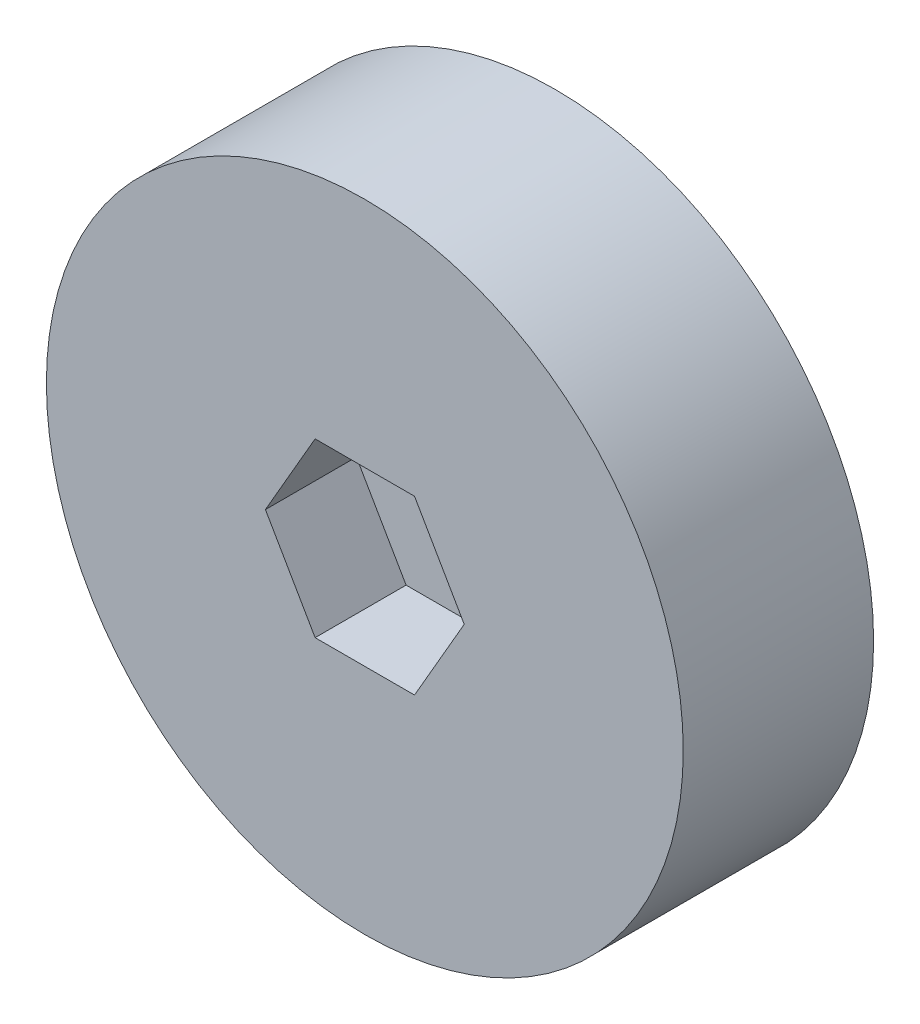
SolidWorks part; units mm, degrees
ref_plane "Front Plane" through (0, 0, 0) normal (0, 0, 1) x (1, 0, 0)
ref_plane "Top Plane" through (0, 0, 0) normal (0, 1, 0) x (1, 0, 0)
ref_plane "Right Plane" through (0, 0, 0) normal (1, 0, 0) x (0, 0, -1)
other "Configuration Table"
sketch "Sketch7" plane through (0, 0, 0) normal (0, 0, 1) x (1, 0, 0)
  circle A0 centre (0, 0) radius 24.25
  dimension "D1" = 48.5
extrude "Boss-Extrude3" [suppressed] add sketch "Sketch7" along normal blind 6.5
sketch "Sketch8" [suppressed] plane through (0, 0, 0) normal (0, 0, -1) x (-1, 0, 0)
  line L1 (3.5507, -6.15) -> (7.1014, 0)
  line L2 (7.1014, 0) -> (3.5507, 6.15)
  line L3 (3.5507, 6.15) -> (-3.5507, 6.15)
  line L4 (-3.5507, 6.15) -> (-7.1014, 0)
  line L5 (-7.1014, 0) -> (-3.5507, -6.15)
  line L6 (-3.5507, -6.15) -> (3.5507, -6.15)
  circle A0 centre (0, 0) radius 6.15 construction
  dimension "D1" = 12.3
extrude "Cut-Extrude4" [suppressed] cut sketch "Sketch8" against normal up to surface (6.5 mm away)
sketch "Sketch9" [suppressed] plane through (0, 0, 0) normal (0, 0, -1) x (-1, 0, 0)
  circle A0 centre (0, 0) radius 24.25 construction
  circle A1 centre (0, 0) radius 24.25
extrude "Boss-Extrude4" [suppressed] add sketch "Sketch9" along normal blind 7.1
sketch "Sketch10" [suppressed] plane through (0, 0, -7.1) normal (0, 0, -1) x (-1, 0, 0)
  circle A0 centre (0, 0) radius 4
  dimension "D1" = 8
extrude "Boss-Extrude5" [suppressed] add sketch "Sketch10" along normal blind 7
sketch "Sketch11" [suppressed] plane through (0, 0, 0) normal (0, 0, 1) x (1, 0, 0)
  circle A0 centre (0, 0) radius 2.2
  dimension "D1" = 4.4
extrude "Cut-Extrude5" [suppressed] cut sketch "Sketch11" against normal up to surface (14.1 mm away)
sketch "Sketch1" plane through (0, 0, 0) normal (0, 0, 1) x (1, 0, 0)
  circle A0 centre (0, 0) radius 7.5
  dimension "D2" = 15
extrude "Boss-Extrude1" [suppressed] add sketch "Sketch1" along normal blind 12
sketch "Sketch2" [suppressed] plane through (0, 0, 12) normal (0, 0, -1) x (-1, 0, 0)
  circle A3 centre (0, 0) radius 9.5
  circle A4 centre (0, 0) radius 9.5
  dimension "D1" = 2
extrude "Boss-Extrude2" [suppressed] add sketch "Sketch2" against normal blind 2
sketch "Sketch3" [suppressed] plane through (0, 0, 0) normal (0, 0, 1) x (1, 0, 0)
  line L1 (3.5507, -6.15) -> (7.1014, 0)
  line L2 (7.1014, 0) -> (3.5507, 6.15)
  line L3 (3.5507, 6.15) -> (-3.5507, 6.15)
  line L4 (-3.5507, 6.15) -> (-7.1014, 0)
  line L5 (-7.1014, 0) -> (-3.5507, -6.15)
  line L6 (-3.5507, -6.15) -> (3.5507, -6.15)
  circle A0 centre (0, 0) radius 6.15 construction
  dimension "D1" = 12.3
extrude "Cut-Extrude1" [suppressed] cut sketch "Sketch3" against normal up to surface (14 mm away)
mirror "Mirror1" [suppressed] about plane through (0, 0, 0) normal (0, 0, 1)
sketch "Sketch5" [suppressed] plane through (0, 0, 0) normal (0, 0, 1) x (1, 0, 0)
  circle A0 centre (0, 0) radius 2.2
  dimension "D1" = 4.4
extrude "Cut-Extrude2" [suppressed] cut sketch "Sketch5" against normal up to surface (14 mm away)
sketch "Sketch6" [suppressed] plane through (0, 0, -14) normal (0, 0, -1) x (-1, 0, 0)
  circle A0 centre (0, 0) radius 6.15
  dimension "D1" = 12.3
extrude "Cut-Extrude3" [suppressed] cut sketch "Sketch6" against normal offset from surface (10 mm away) 4
sketch "Sketch16" plane through (0, 0, 0) normal (0, 0, 1) x (1, 0, 0)
  line L1 (7.1014, 0) -> (3.5507, 6.15)
  line L2 (3.5507, 6.15) -> (-3.5507, 6.15)
  line L3 (-3.5507, 6.15) -> (-7.1014, 0)
  line L4 (-7.1014, 0) -> (-3.5507, -6.15)
  line L5 (-3.5507, -6.15) -> (3.5507, -6.15)
  line L6 (3.5507, -6.15) -> (7.1014, 0)
  circle A0 centre (0, 0) radius 22.75
  circle A1 centre (0, 0) radius 6.15 construction
  dimension "D1" = 45.5
  dimension "D2" = 12.3
extrude "Boss-Extrude9" add sketch "Sketch16" along normal blind 6.5
sketch "Sketch18" plane through (0, 0, 0) normal (0, 0, -1) x (-1, 0, 0)
  circle A0 centre (0, 0) radius 2.25
  circle A1 centre (0, 0) radius 22.75
  circle A2 centre (0, 0) radius 22.75
  dimension "D2" = 4.5
  dimension "D1" = 0
extrude "Boss-Extrude10" add sketch "Sketch18" along normal blind 7.1
sketch "Sketch19" plane through (0, 0, -7.1) normal (0, 0, -1) x (-1, 0, 0)
  circle A0 centre (0, 0) radius 4
  circle A1 centre (0, 0) radius 2.25 construction
  circle A2 centre (0, 0) radius 2.25
  dimension "D1" = 8
extrude "Boss-Extrude11" add sketch "Sketch19" along normal blind 7
